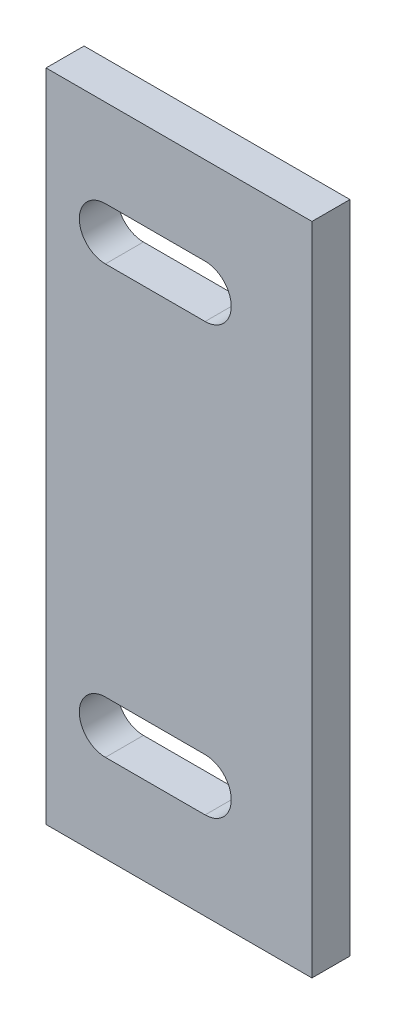
SolidWorks part; units mm, degrees
material "Polyetheretherketone (PEEK)"
ref_plane "Front Plane" through (0, 0, 0) normal (0, 0, 1) x (1, 0, 0)
ref_plane "Top Plane" through (0, 0, 0) normal (0, 1, 0) x (1, 0, 0)
ref_plane "Right Plane" through (0, 0, 0) normal (1, 0, 0) x (0, 0, -1)
ref_plane "Plane1" through (0, 0, 4) normal (0, 0, 1) x (1, 0, 0)
sketch "Sketch1" plane through (0, 0, 4) normal (0, 0, 1) x (1, 0, 0)
  line L0 (-21.75, 25.25) -> (-11.25, 25.25)
  line L1 (-11.25, 19.75) -> (-21.75, 19.75)
  line L2 (-21.75, -19.75) -> (-11.25, -19.75)
  line L3 (-11.25, -25.25) -> (-21.75, -25.25)
  line L4 (-28, -34.5) -> (0, -34.5)
  line L5 (0, -34.5) -> (0, 34.5)
  line L6 (0, 34.5) -> (-28, 34.5)
  line L7 (-28, 34.5) -> (-28, -34.5)
  arc A0 (-11.25, 25.25) -> (-11.25, 19.75) centre (-11.25, 22.5) cw
  arc A1 (-21.75, 19.75) -> (-21.75, 25.25) centre (-21.75, 22.5) cw
  arc A2 (-11.25, -19.75) -> (-11.25, -25.25) centre (-11.25, -22.5) cw
  arc A3 (-21.75, -25.25) -> (-21.75, -19.75) centre (-21.75, -22.5) cw
  dimension "D1" = 2.75
  dimension "D2" = 2.75
  dimension "D3" = 6.25
  dimension "D4" = 16.75
  dimension "D5" = 28
  dimension "D6" = 12
  dimension "D7" = 57
  dimension "D8" = 69
  dimension "D9" = 28
  dimension "D10" = 34.5
extrude "Boss-Extrude1" add sketch "Sketch1" against normal blind 4
